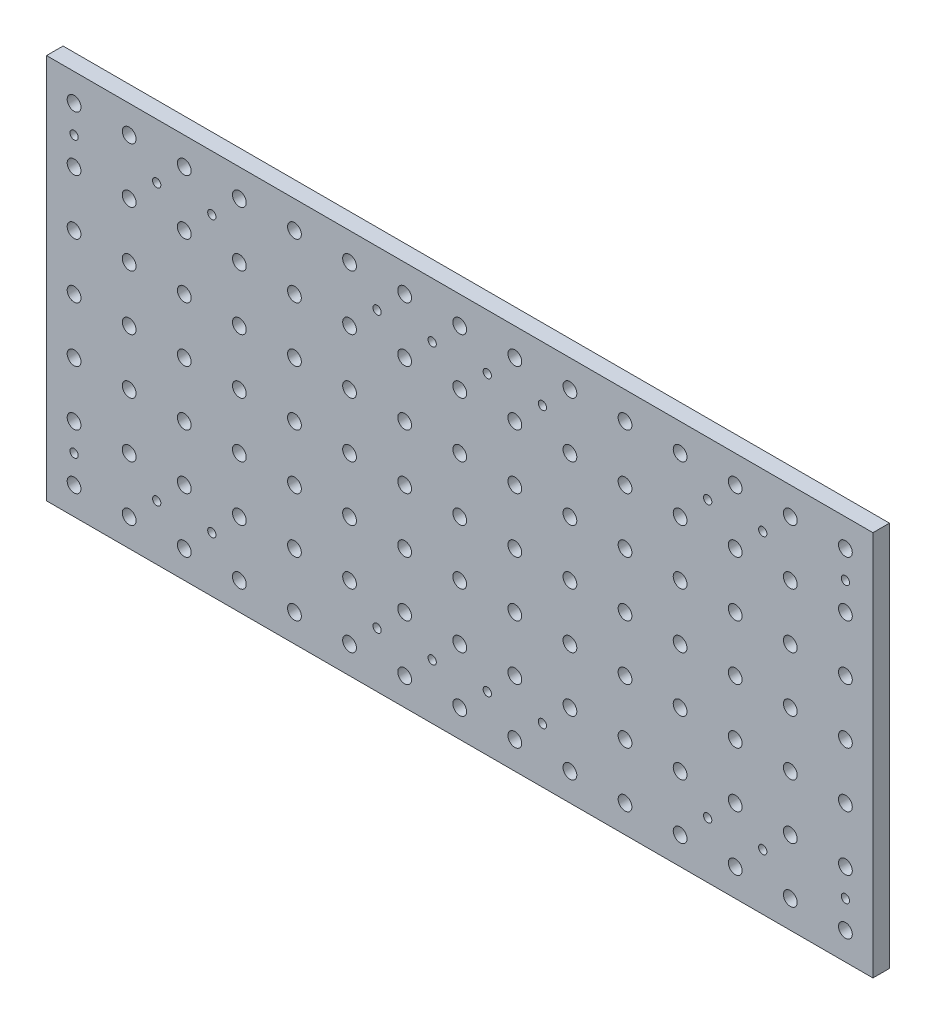
SolidWorks part; units mm, degrees
ref_plane "Ebene vorne" through (0, 0, 0) normal (0, 0, 1) x (1, 0, 0)
ref_plane "Ebene oben" through (0, 0, 0) normal (0, 1, 0) x (1, 0, 0)
ref_plane "Ebene rechts" through (0, 0, 0) normal (1, 0, 0) x (0, 0, -1)
sketch "Skizze1" plane through (0, 0, 0) normal (0, 0, 1) x (1, 0, 0)
  line L1 (-150, 70) -> (150, 70)
  line L2 (-150, 70) -> (-150, -70)
  line L3 (-150, -70) -> (150, -70)
  line L4 (150, 70) -> (150, -70)
  dimension "D1" = 300
  dimension "D2" = 140
  dimension "D3" = 150
  dimension "D4" = 70
extrude "Aufsatz-Linear austragen2" add sketch "Skizze1" along normal blind 6 contours L1 L4 L3 L2
sketch "Skizze2" plane through (0, 0, 0) normal (0, 0, -1) x (-1, 0, 0)
  circle A0 centre (-140, 60) radius 2.5
extrude "Schnitt-Linear austragen1" cut sketch "Skizze2" against normal blind 6
pattern_linear "Lineares Muster1" count 15 spacing 20 along (-1, 0, 0) count 7 spacing 20 along (0, -1, 0) of "Schnitt-Linear austragen1"
sketch "Skizze4" plane through (0, 0, 0) normal (0, 0, -1) x (-1, 0, 0)
  line L0 (-150, 70) -> (-150, -70) construction
  circle A0 centre (-110, 50.3739) radius 1.51
  dimension "D1" = 40
sketch "Skizze5" plane through (0, 0, 0) normal (0, 0, -1) x (-1, 0, 0)
  circle A0 centre (-140, 50) radius 1.5
extrude "Schnitt-Linear austragen3" cut sketch "Skizze5" against normal blind 10
extrude "Cortar-Extruir1" cut sketch "Skizze4" against normal blind 10
pattern_linear "MatrizL1" count 2 spacing 100 along (0, -1, 0) count 2 spacing 20 along (-1, 0, 0) of "Cortar-Extruir1"
pattern_linear "MatrizL2" count 2 spacing 100 along (0, -1, 0) count 2 spacing 280 along (-1, 0, 0) of "Schnitt-Linear austragen3"
sketch "Croquis1" plane through (0, 0, 0) normal (0, 0, -1) x (-1, 0, 0)
  line L0 (150, 70) -> (150, -70) construction
  line L1 (150, 70) -> (-150, 70) construction
  circle A0 centre (110, 50) radius 1.5
  dimension "D1" = 40
  dimension "D2" = 20
extrude "Cortar-Extruir2" cut sketch "Croquis1" against normal blind 10
pattern_linear "MatrizL3" count 2 spacing 100 along (0, -1, 0) count 2 spacing 20 along (1, 0, 0) of "Cortar-Extruir2"
sketch "Croquis2" plane through (0, 0, 0) normal (0, 0, -1) x (-1, 0, 0)
  line L0 (150, 70) -> (-150, 70) construction
  line L1 (150, 70) -> (150, -70) construction
  circle A0 centre (30, 50) radius 1.5
  dimension "D1" = 20
  dimension "D2" = 120
extrude "Cortar-Extruir3" cut sketch "Croquis2" against normal blind 10
pattern_linear "MatrizL4" count 4 spacing 20 along (1, 0, 0) count 2 spacing 100 along (0, -1, 0) of "Cortar-Extruir3"
